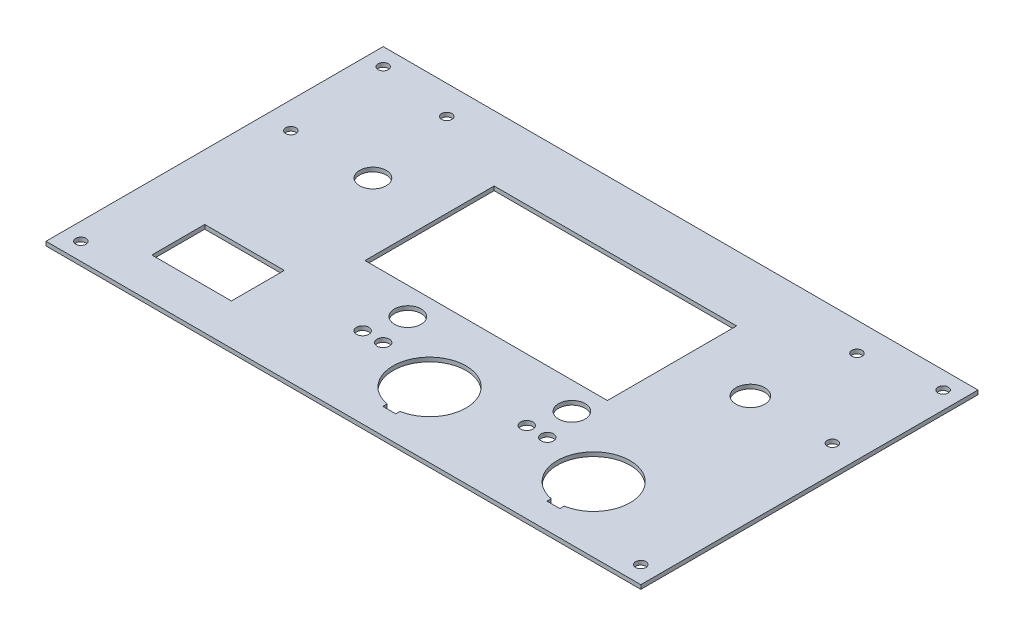
SolidWorks part; units mm, degrees
ref_plane "Front Plane" through (0, 0, 0) normal (0, 0, 1) x (1, 0, 0)
ref_plane "Top Plane" through (0, 0, 0) normal (0, 1, 0) x (1, 0, 0)
ref_plane "Right Plane" through (0, 0, 0) normal (1, 0, 0) x (0, 0, -1)
sketch "Sketch2" plane through (0, 0, 0) normal (0, 1, 0) x (1, 0, 0)
  line L0 (68.25, -36.85) -> (-68.25, -36.85) construction
  line L1 (-72.5, 41.1) -> (72.5, 41.1)
  line L2 (-72.5, 41.1) -> (-72.5, -41.1)
  line L3 (-72.5, -41.1) -> (72.5, -41.1)
  line L4 (72.5, 41.1) -> (72.5, -41.1)
  line L5 (-72.5, 41.1) -> (72.5, -41.1) construction
  line L6 (-72.5, -41.1) -> (72.5, 41.1) construction
  line L7 (5, -46.7164) -> (5, -13.6913) construction
  line L8 (3.425, -33.8595) -> (3.425, -34.9)
  line L9 (3.425, -34.9) -> (6.575, -34.9)
  line L10 (6.575, -34.9) -> (6.575, -33.8595)
  line L11 (43.425, -34.9) -> (43.425, -33.8595)
  line L12 (46.575, -33.8595) -> (46.575, -34.9)
  line L13 (46.575, -34.9) -> (43.425, -34.9)
  line L14 (-56.7, -18.2) -> (-37.3, -18.2)
  line L15 (-56.7, -18.2) -> (-56.7, -31.1)
  line L16 (-56.7, -31.1) -> (-37.3, -31.1)
  line L17 (-37.3, -18.2) -> (-37.3, -31.1)
  line L18 (-56.7, -18.2) -> (-37.3, -31.1) construction
  line L19 (-56.7, -31.1) -> (-37.3, -18.2) construction
  line L20 (45, -42.7164) -> (45, -10.15) construction
  line L21 (-15, -21.4) -> (-10, -21.4) construction
  line L22 (25, -21.4) -> (30, -21.4) construction
  line L23 (0, 41.5549) -> (0, -44.9568) construction
  line L24 (0, -54.076) -> (0, 37.8204) construction
  line L25 (-92.2167, 34.1) -> (85.1121, 34.1) construction
  line L26 (-50, 54.08) -> (-50, -76.7645) construction
  line L29 (-29.55, 25.2) -> (29.55, 25.2)
  line L30 (-29.55, 25.2) -> (-29.55, -6.29)
  line L31 (-29.55, -6.29) -> (29.55, -6.29)
  line L32 (29.55, 25.2) -> (29.55, -6.29)
  line L33 (-29.55, 25.2) -> (29.55, -6.29) construction
  line L34 (-29.55, -6.29) -> (29.55, 25.2) construction
  circle A1 centre (-68.25, -36.85) radius 1.25
  circle A2 centre (68.25, -36.85) radius 1.25
  arc A3 (6.575, -33.8595) -> (3.425, -33.8595) centre (5, -25.1) ccw
  arc A4 (43.425, -33.8595) -> (46.575, -33.8595) centre (45, -25.1) cw
  circle A5 centre (-10, -21.4) radius 1.5
  circle A6 centre (30, -21.4) radius 1.5
  circle A7 centre (-15, -21.4) radius 1.5
  circle A8 centre (25, -21.4) radius 1.5
  circle A9 centre (-12.5, -12.9) radius 3.25
  circle A11 centre (-46, 12.1) radius 3.25
  circle A12 centre (46, 12.1) radius 3.5
  circle A13 centre (-68.25, 36.85) radius 1.25
  circle A14 centre (68.25, 36.85) radius 1.25
  circle A16 centre (-66, 12.1) radius 1.25
  circle A18 centre (-50, 34.1) radius 1.25
  circle A19 centre (66, 12.1) radius 1.25
  circle A20 centre (50, 34.1) radius 1.25
  circle A21 centre (27.5, -12.9) radius 3.25
  point P0 (0, 0)
  point P12 (0, -36.85)
  point P17 (5, -16.2)
  point P20 (5, -34.9)
  point P21 (-47, -24.65)
  point P41 (45, -34.9)
  point P42 (45, -16.2)
  point P43 (-12.5, -21.4)
  point P63 (0, 9.455)
  point P76 (27.5, -21.4)
  dimension "D3" = 136.5
  dimension "D4" = 8.9
  dimension "D10" = 3
  dimension "D21" = 6.5
  dimension "D28" = 7
  dimension "D24" = 2.5
  dimension "D34" = 2.5
  dimension "D1" = 145
  dimension "D2" = 82.2
  dimension "D5" = 3.15
  dimension "D6" = 18.7
  dimension "D7" = 12.9
  dimension "D8" = 8.9
  dimension "D9" = 18.7
  dimension "D11" = 22
  dimension "D12" = 5
  dimension "D13" = 5
  dimension "D14" = 55.5
  dimension "D15" = 5
  dimension "D16" = 45
  dimension "D17" = 10
  dimension "D18" = 47
  dimension "D19" = 16
  dimension "D20" = 4.25
  dimension "D22" = 47
  dimension "D23" = 12.5
  dimension "D25" = 4.25
  dimension "D26" = 27.5
  dimension "D27" = 46
  dimension "D29" = 46
  dimension "D30" = 19.4
  dimension "D31" = 59.1
  dimension "D32" = 31.49
  dimension "D35" = 7
  dimension "D36" = 22
  dimension "D37" = 50
  dimension "D38" = 66
extrude "Boss-Extrude1" add sketch "Sketch2" along normal blind 1
